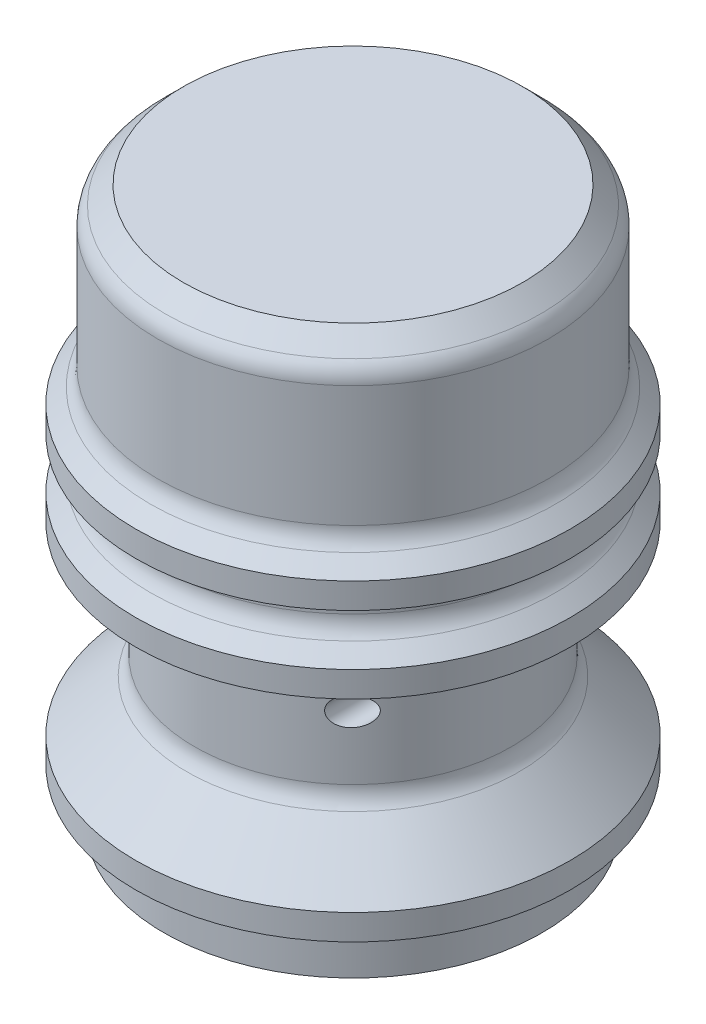
SolidWorks part; units mm, degrees
ref_plane "Plano frontal" through (0, 0, 0) normal (0, 0, 1) x (1, 0, 0)
ref_plane "Plano superior" through (0, 0, 0) normal (0, 1, 0) x (1, 0, 0)
ref_plane "Plano direito" through (0, 0, 0) normal (1, 0, 0) x (0, 0, -1)
sketch "Cut_1" plane through (0, 0, 0) normal (0, 1, 0) x (1, 0, 0)
  line L0 (4.658, 6.0576) -> (4.658, 2.8486) construction
  line L1 (3.856, 3.8656) -> (3.856, 6.5972)
  line L2 (5.46, 0) -> (5.46, 5.346)
  line L3 (3.856, 3.8656) -> (4.658, 3.8656) construction
  line L4 (4.658, 3.8656) -> (5.46, 3.8656) construction
  circle A0 centre (0, 0) radius 5.46
  circle A2 centre (0, 0) radius 7.6414
  circle A4 centre (0, 0) radius 3.105
  dimension "D1" = 10.92
  dimension "D5" = 15.2829
  dimension "D6" = 6.21
  dimension "D2" = 4.658
  dimension "D3" = 1.604
  dimension "D4" = 3.209
  dimension "D7" = 0.802
sketch "Cut_2" plane through (0, 0, 0) normal (0, 1, 0) x (1, 0, 0)
  line L0 (4.889, 0) -> (4.889, 3.8203)
  line L1 (3.797, 3.0798) -> (3.797, 4.9071)
  line L2 (3.797, 3.0798) -> (4.343, 3.0798) construction
  line L3 (4.343, 3.0798) -> (4.889, 3.0798) construction
  line L4 (4.343, 4.4311) -> (4.343, 2.2451) construction
  circle A0 centre (0, 0) radius 4.889
  circle A1 centre (0, 0) radius 6.2046
  circle A2 centre (0, 0) radius 4.889
  circle A3 centre (0, 0) radius 5.798
  dimension "D1" = 9.778
  dimension "D2" = 4.343
  dimension "D5" = 12.4091
  dimension "D6" = 9.778
  dimension "D7" = 11.596
  dimension "D3" = 1.092
  dimension "D4" = 2.186
  dimension "D8" = 0.546
sketch "Esboço4" plane through (0, 0, 0) normal (0, 0, 1) x (1, 0, 0)
  line L0 (0, 0) -> (0, 9.8449) construction
  line L1 (4.889, 0) -> (4.889, 4.889) construction
  line L2 (3.105, 1) -> (3.105, 10.329)
  line L3 (3.105, 10.329) -> (5.46, 12.684)
  line L4 (5.46, 12.684) -> (5.46, 19.658)
  line L5 (5.46, 19.658) -> (0, 19.658)
  line L6 (0, 19.658) -> (0, 21.658)
  line L7 (0, 21.658) -> (7.6414, 21.658)
  line L8 (7.6414, 21.658) -> (7.6414, 10.732)
  line L9 (7.6414, 10.732) -> (6.2046, 10.732)
  line L10 (6.2046, 10.732) -> (6.2046, 4)
  line L11 (6.2046, 4) -> (7.4, 4)
  line L12 (7.4, 4) -> (7.4, 0)
  line L13 (7.4, 0) -> (5.798, 0)
  line L14 (4.889, 4.4734) -> (4.889, 4.889)
  line L16 (4.889, 4.889) -> (4.889, 9.232)
  line L17 (4.889, 9.232) -> (4.105, 9.232)
  line L18 (4.105, 9.232) -> (4.105, 1)
  line L19 (4.105, 1) -> (3.105, 1)
  line L21 (6.2046, 4) -> (6.2046, 0) construction
  line L22 (5.798, 0) -> (5.798, 2.899)
  line L23 (4.889, 0) -> (-4.889, 0) construction
  line L24 (5.798, 2.899) -> (4.889, 4.4734)
  line L25 (5.46, 12.684) -> (5.46, 0) construction
  line L26 (3.105, 1) -> (3.105, 0) construction
  line L28 (7.6414, 10.732) -> (7.6414, 0) construction
  line L29 (4.889, 4.4734) -> (4.889, 0) construction
  line L32 (0, 9.232) -> (4.28, 9.232) construction
  dimension "D1" = 1
  dimension "D2" = 14.8
  dimension "D3" = 1
  dimension "D4" = 4
  dimension "D5" = 45
  dimension "D6" = 9.329
  dimension "D7" = 4.343
  dimension "D8" = 2
  dimension "D9" = 30
  dimension "D10" = 9.329
  dimension "D11" = 1.5
  dimension "D12" = 4.889
  dimension "D13" = 1.1954
  dimension "D14" = 4.28
  dimension "D16" = 2.899
revolve "Revolução1" add sketch "Esboço4" angle 360 about L0
sketch "Esboço5" plane through (0, 0, 0) normal (0, 0, 1) x (1, 0, 0)
  line L0 (0, 0) -> (0, 18.356) construction
  line L1 (4.889, 0) -> (-4.889, 0) construction
  line L2 (0, 18.356) -> (0, 19.658) construction
  line L3 (0, 18.356) -> (4.658, 18.356) construction
  line L4 (4.658, 18.356) -> (4.658, 0) construction
  line L5 (-5.46, 19.658) -> (5.46, 19.658) construction
  line L6 (-4.105, 0) -> (-4.105, 8.186) construction
  line L7 (5.46, 0) -> (-5.46, 0) construction
  line L8 (-4.105, 8.186) -> (-4.105, 9.232) construction
  line L9 (-4.105, 8.186) -> (-4.343, 8.186) construction
  line L10 (-4.343, 8.186) -> (-4.343, 0) construction
  line L15 (-4.343, 0) -> (0, 0) construction
  line L16 (0, 0) -> (4.343, 0) construction
  line L17 (4.889, 0) -> (-4.889, 0) construction
  circle A0 centre (4.658, 18.356) radius 0.802
  circle A1 centre (-4.343, 8.186) radius 0.546
  dimension "D1" = 1.604
  dimension "D3" = 1.092
  dimension "D2" = 1.302
  dimension "D4" = 1.046
extrude "Inlet_1" [suppressed] cut sketch "Esboço5" against normal through all contours A0
pattern_circular "PadrãoCircular1" [suppressed] count 4 over 360
ref_plane "Plano1" through (0, 0, -10) normal (0, 0, 1) x (1, 0, 0)
sketch "Esboço9" plane through (0, 0, -10) normal (0, 0, 1) x (1, 0, 0)
  circle A0 centre (-4.343, 8.186) radius 0.546
  circle A1 centre (-4.343, 8.186) radius 0.546 construction
extrude "Corte-extrusão1" cut sketch "Esboço9" along normal up to surface (6.9202 mm away) contours A0
pattern_circular "PadrãoCircular2" count 4 over 360 of "Corte-extrusão1"
chamfer "Chanfro1" distance 1 angle 45 1 edges at (0, 21.658, -7.6414)
fillet "Filete3" radius 1 1 edges at (0, 20.658, 7.6414)
fillet "Filete_topo" radius 0.35 3 edges at (0, 9.232, -4.105) (0, 9.232, -4.889) (0, 19.658, -5.46)
fillet "Filete_base" radius 2 4 edges at (0, 10.329, -3.105) (0, 12.684, -5.46) (0, 4.4734, -4.889) (0, 2.899, -5.798)
sketch "Esboço11" plane through (0, 0, 0) normal (0, 0, 1) x (1, 0, 0)
  line L0 (6.2046, 10.232) -> (8.5, 10.232)
  line L1 (8.5, 10.232) -> (8.5, 11.232)
  line L2 (8.5, 11.232) -> (7.6414, 12.0906)
  line L3 (7.6414, 12.0906) -> (7.6414, 13.232)
  line L4 (7.6414, 13.232) -> (8.5, 13.232)
  line L5 (8.5, 13.232) -> (8.5, 14.232)
  line L6 (8.5, 14.232) -> (7.6414, 15.0906)
  line L7 (7.6414, 15.0906) -> (7.1414, 15.0906)
  line L8 (7.1414, 15.0906) -> (7.1414, 11.232)
  line L9 (7.1414, 11.232) -> (5.7046, 11.232)
  line L10 (5.7046, 11.232) -> (5.7046, 10.232)
  line L11 (5.7046, 10.232) -> (6.2046, 10.232)
  line L12 (7.4, 2) -> (8.5, 2)
  line L13 (8.5, 2) -> (8.5, 3)
  line L14 (8.5, 3) -> (6.2046, 5.2954)
  line L15 (6.2046, 5.2954) -> (5.7046, 5.2954)
  line L16 (5.7046, 5.2954) -> (5.7046, 4)
  line L17 (5.7046, 4) -> (6.9, 2)
  line L18 (6.9, 2) -> (7.4, 2)
  line L19 (7.6414, 15.0906) -> (7.6414, 10.732) construction
  line L20 (5.7046, 4) -> (6.2046, 4) construction
  line L22 (6.2046, 10.232) -> (6.2046, 10.732) construction
  line L23 (6.2046, 10.732) -> (6.2046, 11.232) construction
  line L26 (0, 0) -> (0, 7.0334) construction
  line L27 (7.4, 2) -> (7.4, 0) construction
  line L30 (6.2046, 5.2954) -> (6.2046, 4) construction
  dimension "D1" = 0.5
  dimension "D2" = 0.5
  dimension "D3" = 1
  dimension "D4" = 4
  dimension "D5" = 45
  dimension "D6" = 0.5
  dimension "D7" = 0.5
  dimension "D8" = 17
  dimension "D9" = 0.5
  dimension "D10" = 2
  dimension "D11" = 0.5
  dimension "D12" = 45
  dimension "D13" = 1
  dimension "D15" = 0.8586
  dimension "D16" = 1.1414
revolve "Revolução2" add sketch "Esboço11" angle 360 about L26
fillet "Filete4" radius 1 4 edges at (0, 12.0906, -7.6414) (0, 15.0906, 7.6414) (0, 5.2954, 6.2046) (0, 10.232, -6.2046)
fillet "Filete5" radius 0.5 2 edges at (0, 2, -7.4) (0, 13.232, -7.6414)
sketch "Esboço12" plane through (0, 0, 0) normal (0, 0, 1) x (1, 0, 0)
  line L0 (-3.7559, 1) -> (-3.7559, 10.0858)
  line L1 (-3.7559, 10.0858) -> (-6.6937, 13.5436)
  line L2 (-6.6937, 13.5436) -> (-6.6937, 20.4631)
  line L3 (-6.6937, 20.4631) -> (0, 20.4631)
  line L4 (0, 20.4631) -> (0, 1)
  line L5 (0, 1) -> (-3.7559, 1)
  line L6 (0, 0) -> (0, -2.4571) construction
  line L7 (-4.105, 1) -> (4.105, 1) construction
  point P8 (-3.292, 1.0102)
  point P10 (-3.7559, 0.8442)
  dimension "D1" = 6.6937
  dimension "D2" = 40.351
  dimension "D3" = 7.5118
  dimension "D4" = 9.0858
  dimension "D5" = 6.9195
revolve "Revolução3" add sketch "Esboço12" angle 360 about L6
sketch "Esboço13" plane through (0, 1, 0) normal (0, -1, 0) x (1, 0, 0)
  circle A0 centre (0, 0) radius 4.455
  circle A2 centre (0, 0) radius 4.455 construction
extrude "Corte-extrusão3" cut sketch "Esboço13" against normal up to surface (8.232 mm away) contours A0 up to face at (0, 9.232, -4.455)
equation "\"D2@Esboço5\"=\"D1@Esboço5\"/2+0.5"
equation "\"D4@Esboço5\"=\"D3@Esboço5\"/2+0.5"
